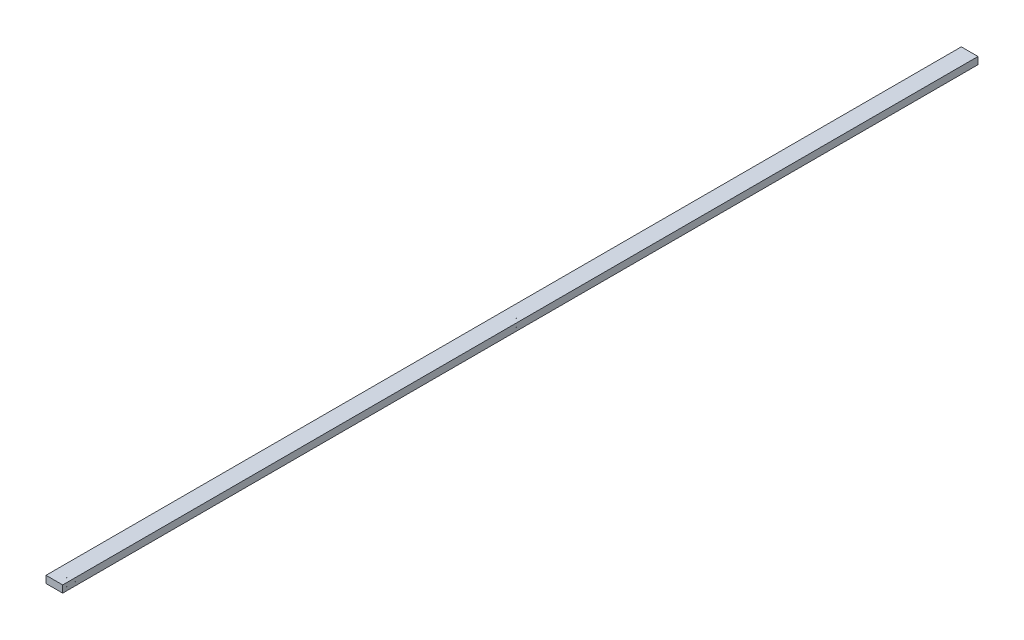
SolidWorks part; units mm, degrees
material "Pine"
ref_plane "Front Plane" through (0, 0, 0) normal (0, 0, 1) x (1, 0, 0)
ref_plane "Top Plane" through (0, 0, 0) normal (0, 1, 0) x (1, 0, 0)
ref_plane "Right Plane" through (0, 0, 0) normal (1, 0, 0) x (0, 0, -1)
sketch "Sketch1" plane through (0, 0, 0) normal (0, 0, 1) x (1, 0, 0)
  line L1 (0, 0) -> (88.9, 0)
  line L2 (0, 0) -> (0, 38.1)
  line L3 (0, 38.1) -> (88.9, 38.1)
  line L4 (88.9, 0) -> (88.9, 38.1)
  dimension "D1" = 88.9
  dimension "D2" = 38.1
extrude "Boss-Extrude1" add sketch "Sketch1" along normal blind 4876.8
sketch "Sketch3" plane through (0, 0, 0) normal (0, -1, 0) x (1, 0, 0)
  line L0 (88.9, 4832.35) -> (44.45, 4832.35) construction
  line L3 (88.9, 4876.8) -> (88.9, 0) construction
  line L6 (44.45, 4832.35) -> (0, 4832.35) construction
  line L7 (0, 4876.8) -> (0, 0) construction
  line L8 (44.45, 4832.35) -> (44.45, 4876.8) construction
  line L9 (0, 4876.8) -> (88.9, 4876.8) construction
  line L10 (88.9, 2438.4) -> (44.45, 2438.4) construction
  line L11 (44.45, 2438.4) -> (0, 2438.4) construction
  circle A0 centre (66.675, 4832.35) radius 0.889
  circle A1 centre (22.225, 4832.35) radius 0.889
  circle A2 centre (22.225, 2438.4) radius 0.889
  circle A3 centre (66.675, 2438.4) radius 0.889
  circle A4 centre (66.675, 44.45) radius 0.889
  circle A5 centre (22.225, 44.45) radius 0.889
  dimension "D2" = 1.778
  dimension "D1" = 44.45
extrude "Cut-Extrude2" cut sketch "Sketch3" against normal up to surface (38.1 mm away) up to face at (44.45, 38.1, 2438.4)
sketch "Sketch5" plane through (88.9, 0, 0) normal (1, 0, 0) x (0, 0, -1)
  line L0 (-4876.8, 19.05) -> (-4832.35, 19.05) construction
  line L1 (-4876.8, 0) -> (-4876.8, 38.1) construction
  line L2 (-4832.35, 19.05) -> (-4787.9, 19.05) construction
  line L3 (-2438.4, 38.1) -> (-2438.4, 0) construction
  line L4 (-4876.8, 38.1) -> (0, 38.1) construction
  line L5 (-2438.4, 19.05) -> (-2482.85, 19.05) construction
  line L6 (-2438.4, 19.05) -> (-2393.95, 19.05) construction
  line L7 (-4876.8, 0) -> (0, 0) construction
  circle A0 centre (-4854.575, 19.05) radius 0.889
  circle A1 centre (-4810.125, 19.05) radius 0.889
  circle A2 centre (-2460.625, 19.05) radius 0.889
  circle A3 centre (-2416.175, 19.05) radius 0.889
  circle A4 centre (-22.225, 19.05) radius 0.889
  circle A5 centre (-66.675, 19.05) radius 0.889
  dimension "D2" = 1.778
  dimension "D1" = 88.9
  dimension "D3" = 88.9
extrude "Cut-Extrude3" cut sketch "Sketch5" against normal up to surface (88.9 mm away) up to face at (0, 19.05, 2438.4)
equation "\"length\"= 12 * 16"
equation "\"D1@Boss-Extrude1\"=\"length\""
